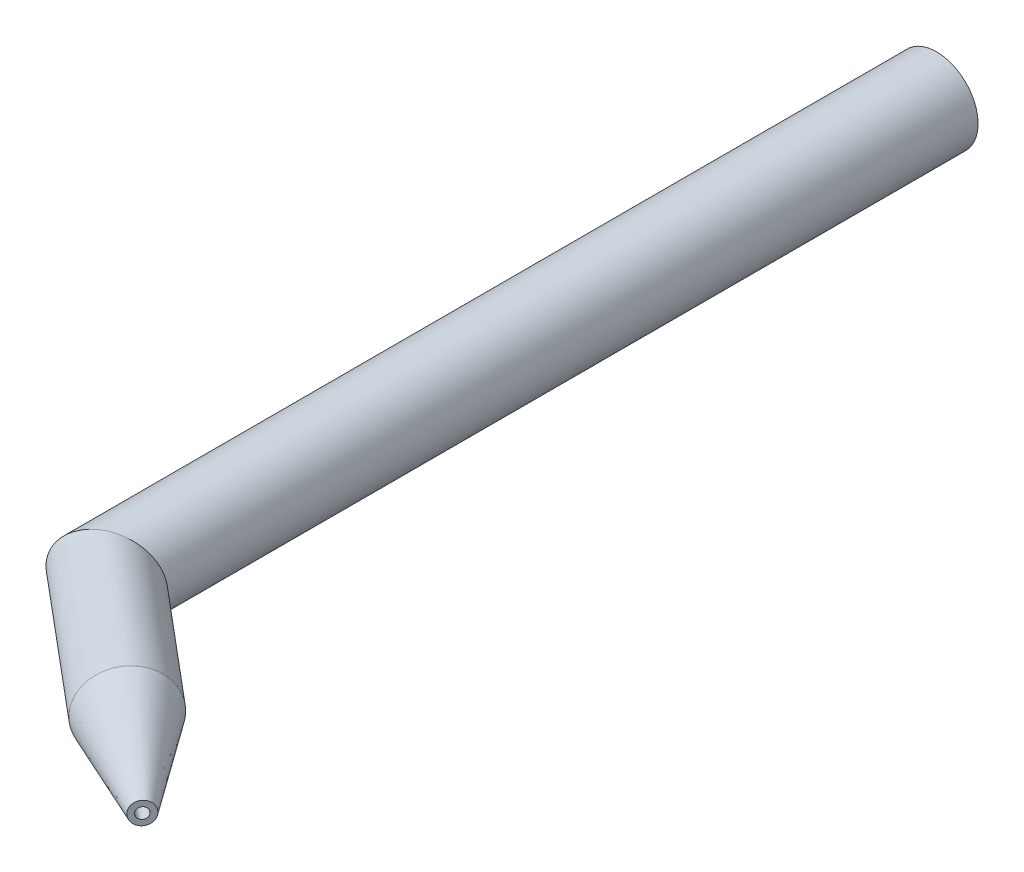
SolidWorks part; units mm, degrees
ref_plane "前视基准面" through (0, 0, 0) normal (0, 0, 1) x (1, 0, 0)
ref_plane "上视基准面" through (0, 0, 0) normal (0, 1, 0) x (1, 0, 0)
ref_plane "右视基准面" through (0, 0, 0) normal (1, 0, 0) x (0, 0, -1)
sketch "草图1" plane through (0, 0, 0) normal (0, 0, 1) x (1, 0, 0)
  circle A0 centre (0, 0) radius 7.5
  circle A1 centre (0, 0) radius 4.5
  dimension "D1" = 9
  dimension "D2" = 15
extrude "凸台-拉伸1" add sketch "草图1" along normal blind 100
sketch "草图2" plane through (0, 0, 0) normal (0, 1, 0) x (1, 0, 0)
  line L0 (0, -100) -> (0, -130)
  line L1 (-7.5, -100) -> (7.5, -100) construction
  line L2 (0, -130) -> (22.9813, -149.2836)
  dimension "D1" = 130
  dimension "D2" = 30
sketch "草图3" plane through (0, 0, 100) normal (0, 0, 1) x (1, 0, 0)
  circle A0 centre (0, 0) radius 7.5
  circle A1 centre (0, 0) radius 4.5
  dimension "D1" = 9
sweep "扫描1" add profiles "草图3" path "草图2"
sketch "草图5" plane through (0, 0, 0) normal (0, 1, 0) x (1, 0, 0)
  line L0 (0, -130) -> (39.5707, -163.2038) construction
  line L1 (-7.5, -133.4973) -> (7.5, -126.5027) construction
  line L2 (0, 0) -> (0, -130) construction
  line L3 (27.8022, -143.5383) -> (25.8739, -145.8364)
  line L4 (18.1604, -155.029) -> (27.8022, -143.5383) construction
  line L5 (25.8739, -145.8364) -> (33.6303, -156.9138)
  line L7 (27.8022, -143.5383) -> (35.7287, -154.4481)
  line L9 (33.6303, -156.9138) -> (40.5225, -162.697)
  line L10 (35.7287, -154.4481) -> (41.1653, -161.931)
  line L11 (41.1653, -161.931) -> (40.5225, -162.697)
  dimension "D1" = 130
  dimension "D2" = 3
  dimension "D3" = 75
  dimension "D4" = 1
  dimension "D5" = 1
  dimension "D6" = 76
revolve "旋转1" add sketch "草图5" angle 360 about L0
sketch "草图6" plane through (0, 0, 0) normal (0, 0, -1) x (-1, 0, 0)
  circle A0 centre (0, 0) radius 4.5
  circle A1 centre (0, 0) radius 7.5
extrude "凸台-拉伸2" add sketch "草图6" along normal blind 20
